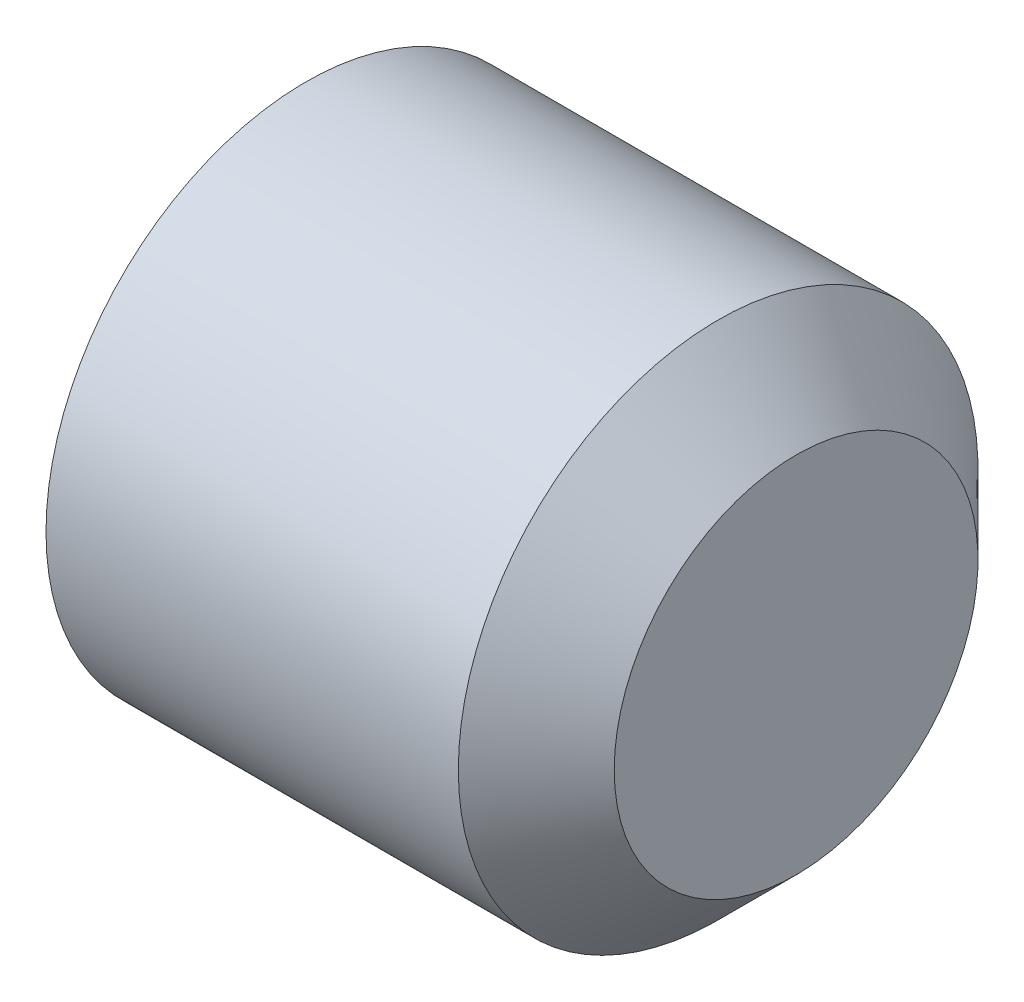
SolidWorks part; units mm, degrees
ref_plane "Front Plane" through (0, 0, 0) normal (0, 0, 1) x (1, 0, 0)
ref_plane "Top Plane" through (0, 0, 0) normal (0, 1, 0) x (1, 0, 0)
ref_plane "Right Plane" through (0, 0, 0) normal (1, 0, 0) x (0, 0, -1)
ref_plane "Plane1" through (-5, 0, 0) normal (1, 0, 0) x (0, 0, -1)
sketch "Sketch1" plane through (0, 0, 0) normal (0, 0, 1) x (1, 0, 0)
  line L0 (-5, 0) -> (0, 0) construction
  line L1 (0, 0) -> (0, 1.75)
  line L2 (-0.75, 2.5) -> (-4.7171, 2.5)
  line L3 (-5, 2.01) -> (-5, 0)
  line L4 (-5, 0) -> (0, 0)
  line L5 (0, 1.75) -> (-0.75, 2.5)
  line L6 (-5, 2.01) -> (-4.7171, 2.5)
  point P4 (0, -1.75)
  point P6 (-4.7171, -2.5)
  point P11 (-5, -2.01)
  dimension "L_1" = 5
  dimension "FIX_1" = 60
  dimension "FIX_2" = 45
  dimension "MSM_21" = 3.5
  dimension "KSS_1" = 4.02
  dimension "M_1" = 5
revolve "Revolve1" add sketch "Sketch1" angle 360 about L0
cosmetic thread "Thread401" parameters "ATD"=4.459
sketch "Sketch2" plane through (-5, 0, 0) normal (1, 0, 0) x (0, 0, -1)
  line L1 (1.25, -0.7217) -> (1.25, 0.7217)
  line L2 (1.25, 0.7217) -> (0, 1.4434)
  line L3 (0, 1.4434) -> (-1.25, 0.7217)
  line L4 (-1.25, 0.7217) -> (-1.25, -0.7217)
  line L5 (-1.25, -0.7217) -> (0, -1.4434)
  line L6 (0, -1.4434) -> (1.25, -0.7217)
  circle A0 centre (0, 0) radius 1.25 construction
  dimension "MSM_23" = 2.5
extrude "Cut-Extrude1" cut sketch "Sketch2" along normal blind 2
equation "\"KSS_1@Sketch1\"= iif ( ( \"M_1@Sketch1\" = 3 ) , 2.388 , iif ( ( \"M_1@Sketch1\" = 4 ) , 3.142 , 4.02 ) )"
